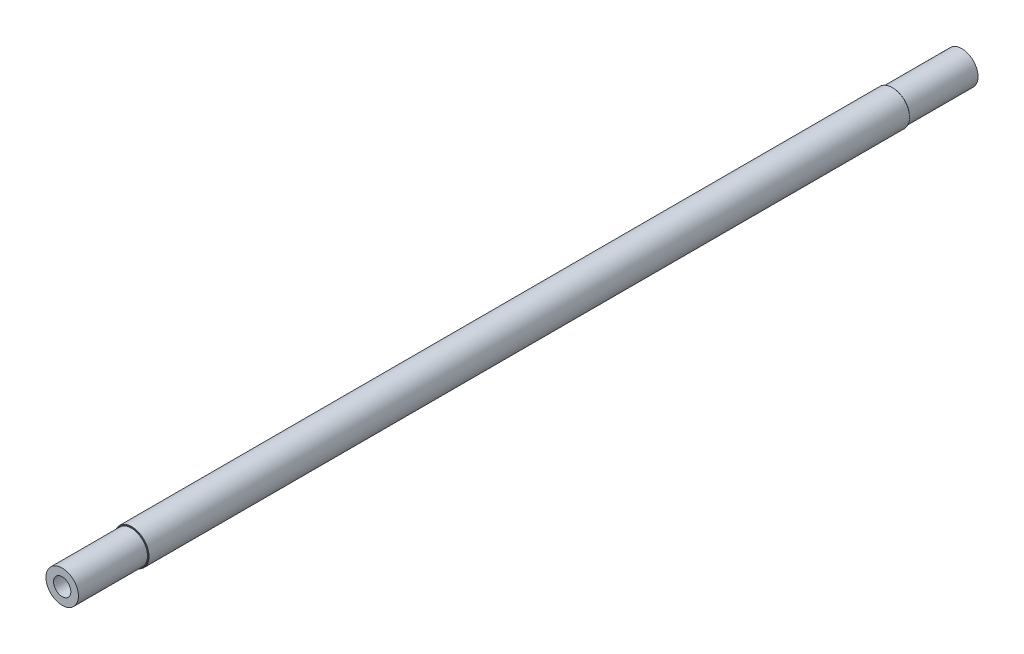
SolidWorks part; units mm, degrees
material "45"
ref_plane "前视基准面" through (0, 0, 0) normal (0, 0, 1) x (1, 0, 0)
ref_plane "上视基准面" through (0, 0, 0) normal (0, 1, 0) x (1, 0, 0)
ref_plane "右视基准面" through (0, 0, 0) normal (1, 0, 0) x (0, 0, -1)
sketch "草图1" plane through (0, 0, 0) normal (0, 0, 1) x (1, 0, 0)
  circle A0 centre (0, 0) radius 40
  circle A1 centre (0, 0) radius 20
  dimension "D1" = 80
  dimension "D2" = 40
extrude "凸台-拉伸1" add sketch "草图1" along normal blind 2082
sketch "草图2" plane through (0, 0, 0) normal (0, 0, -1) x (-1, 0, 0)
  circle A0 centre (0, 0) radius 40
  circle A1 centre (0, 0) radius 37.5
  dimension "D1" = 75
  dimension "D2" = 80
extrude "切除-拉伸1" cut sketch "草图2" against normal blind 160
sketch "草图3" plane through (0, 0, 2082) normal (0, 0, 1) x (1, 0, 0)
  circle A0 centre (0, 0) radius 40
  circle A1 centre (0, 0) radius 37.5
  dimension "D1" = 75
  dimension "D2" = 80
extrude "切除-拉伸2" cut sketch "草图3" against normal blind 160
chamfer "倒角1" distance 1 angle 45 2 edges at (40, 0, 1922) (-40, 0, 160)
